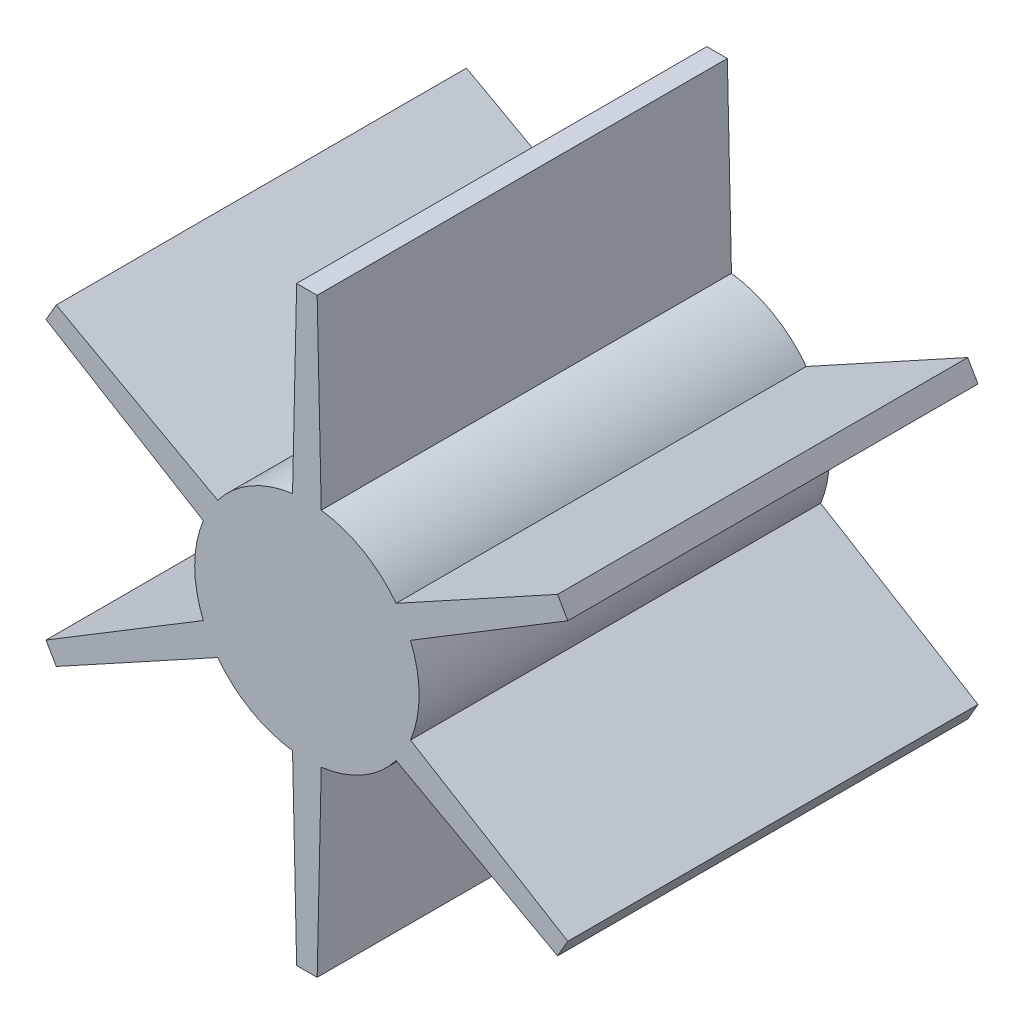
SolidWorks part; units mm, degrees
ref_plane "Front Plane" through (0, 0, 0) normal (0, 0, 1) x (1, 0, 0)
ref_plane "Top Plane" through (0, 0, 0) normal (0, 1, 0) x (1, 0, 0)
ref_plane "Right Plane" through (0, 0, 0) normal (1, 0, 0) x (0, 0, -1)
sketch "Sketch1" plane through (0, 0, 0) normal (0, 0, 1) x (1, 0, 0)
  line L1 (0, 72) -> (-62.3538, 36) construction
  line L2 (-62.3538, 36) -> (-62.3538, -36) construction
  line L3 (-62.3538, -36) -> (0, -72) construction
  line L4 (0, -72) -> (62.3538, -36) construction
  line L5 (62.3538, -36) -> (62.3538, 36) construction
  line L6 (62.3538, 36) -> (0, 72) construction
  line L7 (2.5, 72) -> (-2.5, 72)
  line L10 (0, 72) -> (0, 62.3538) construction
  line L16 (2.5, 72) -> (3.5, 27.129)
  line L18 (-2.5, 72) -> (-3.5, 27.129)
  line L22 (63.6038, 33.8349) -> (25.2444, 10.5334)
  line L23 (61.1038, 38.1651) -> (21.7444, 16.5956)
  line L24 (63.6038, 33.8349) -> (61.1038, 38.1651)
  line L25 (61.1038, -38.1651) -> (21.7444, -16.5956)
  line L26 (63.6038, -33.8349) -> (25.2444, -10.5334)
  line L27 (61.1038, -38.1651) -> (63.6038, -33.8349)
  line L28 (-2.5, -72) -> (-3.5, -27.129)
  line L29 (2.5, -72) -> (3.5, -27.129)
  line L30 (-2.5, -72) -> (2.5, -72)
  line L31 (-63.6038, -33.8349) -> (-25.2444, -10.5334)
  line L32 (-61.1038, -38.1651) -> (-21.7444, -16.5956)
  line L33 (-63.6038, -33.8349) -> (-61.1038, -38.1651)
  line L34 (-61.1038, 38.1651) -> (-21.7444, 16.5956)
  line L35 (-63.6038, 33.8349) -> (-25.2444, 10.5334)
  line L36 (-61.1038, 38.1651) -> (-63.6038, 33.8349)
  circle A0 centre (0, 0) radius 62.3538 construction
  circle A1 centre (0, 0) radius 27.3538
  point P37 (0, 0)
  dimension "D1" = 72
  dimension "D2" = 35
  dimension "D3" = 2.5
  dimension "D4" = 5
  dimension "D5" = 7
extrude "Boss-Extrude1" add sketch "Sketch1" along normal blind 100
